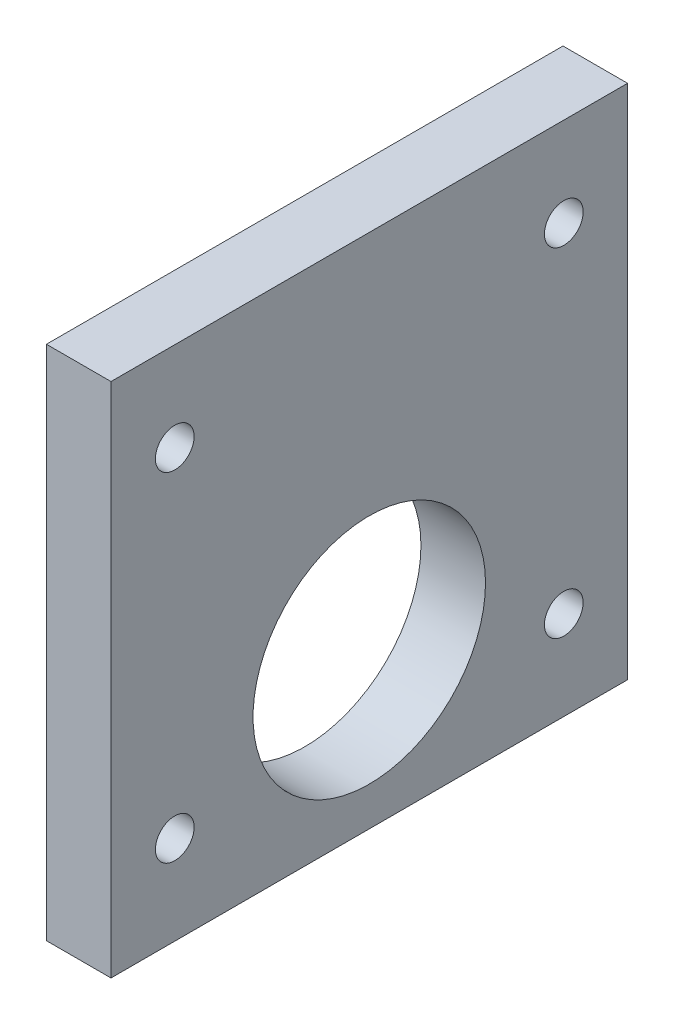
SolidWorks part; units mm, degrees
ref_plane "Front Plane" through (0, 0, 0) normal (0, 0, 1) x (1, 0, 0)
ref_plane "Top Plane" through (0, 0, 0) normal (0, 1, 0) x (1, 0, 0)
ref_plane "Right Plane" through (0, 0, 0) normal (1, 0, 0) x (0, 0, -1)
sketch "Sketch1" plane through (0, 0, 0) normal (1, 0, 0) x (0, 0, -1)
  line L0 (13.7472, 0) -> (13.7472, -40)
  line L1 (13.7472, 0) -> (53.7472, 0)
  line L2 (33.7472, -31.3415) -> (33.7472, -35.2226) construction
  line L3 (13.7472, -40) -> (53.7472, -40)
  line L4 (13.7472, 51.5116) -> (13.7472, -185.1316) construction
  line L5 (13.7472, -20) -> (21.6253, -20) construction
  line L6 (52, 0) -> (60.882, -17.7639) construction
  line L7 (52, 240) -> (52, -360) construction
  line L8 (53.7472, 0) -> (53.7472, -40)
  line L9 (25.8798, -23.6292) -> (41.6146, -32.3708) construction
  circle A0 centre (33.7472, -28) radius 9
  circle A1 centre (18.6851, -6.8993) radius 1.5
  circle A2 centre (18.6851, -33.1007) radius 1.5
  circle A3 centre (48.8093, -33.1007) radius 1.5
  circle A4 centre (48.8093, -6.8993) radius 1.5
  point P20 (18.6851, -6.8993)
  dimension "D3" = 18
  dimension "D4" = 20
  dimension "D5" = 12
  dimension "D1" = 40
  dimension "D6" = 3
  dimension "D2" = 40
extrude "Boss-Extrude1" add sketch "Sketch1" along normal blind 5
